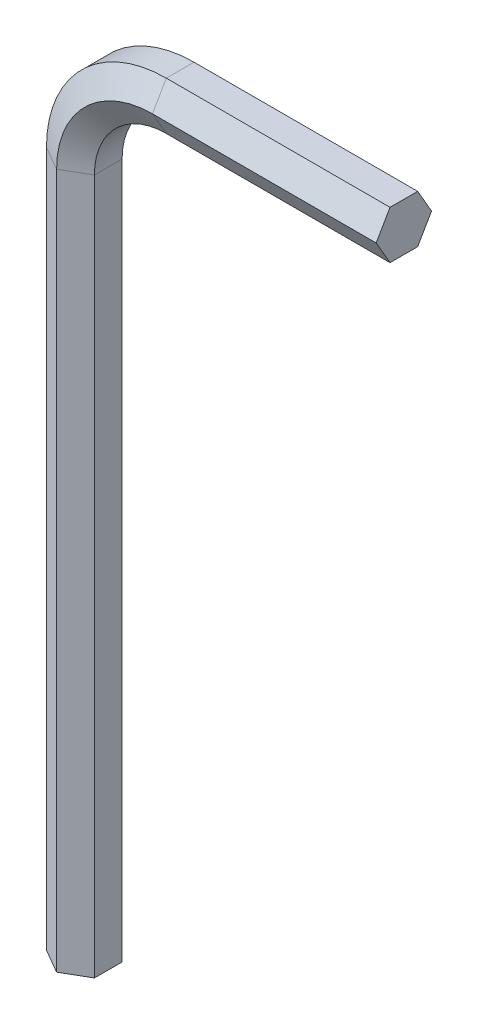
SolidWorks part; units mm, degrees
ref_plane "Front Plane" through (0, 0, 0) normal (0, 0, 1) x (1, 0, 0)
ref_plane "Top Plane" through (0, 0, 0) normal (0, 1, 0) x (1, 0, 0)
ref_plane "Right Plane" through (0, 0, 0) normal (1, 0, 0) x (0, 0, -1)
sketch "Sketch3" plane through (0, 0, 0) normal (0, 0, 1) x (1, 0, 0)
  line L0 (-31.1529, -31.7352) -> (-31.1529, 23.5329)
  line L1 (-23.5329, 31.1529) -> (-5.7529, 31.1529)
  arc A0 (-31.1529, 23.5329) -> (-23.5329, 31.1529) centre (-23.5329, 23.5329) cw
  dimension "D1" = 7.62
sketch "Sketch5" plane through (0, 0, 0) normal (0, 1, 0) x (1, 0, 0)
  line L0 (-31.1529, 0) -> (-23.5329, 0) construction
  line L1 (-31.1529, 2.1997) -> (-33.0579, 1.0999)
  line L2 (-33.0579, 1.0999) -> (-33.0579, -1.0999)
  line L3 (-33.0579, -1.0999) -> (-31.1529, -2.1997)
  line L4 (-31.1529, -2.1997) -> (-29.2479, -1.0999)
  line L5 (-29.2479, -1.0999) -> (-29.2479, 1.0999)
  line L6 (-29.2479, 1.0999) -> (-31.1529, 2.1997)
  circle A0 centre (-31.1529, 0) radius 1.905 construction
sweep "Sweep1" add profiles "Sketch5" path "Sketch3"
